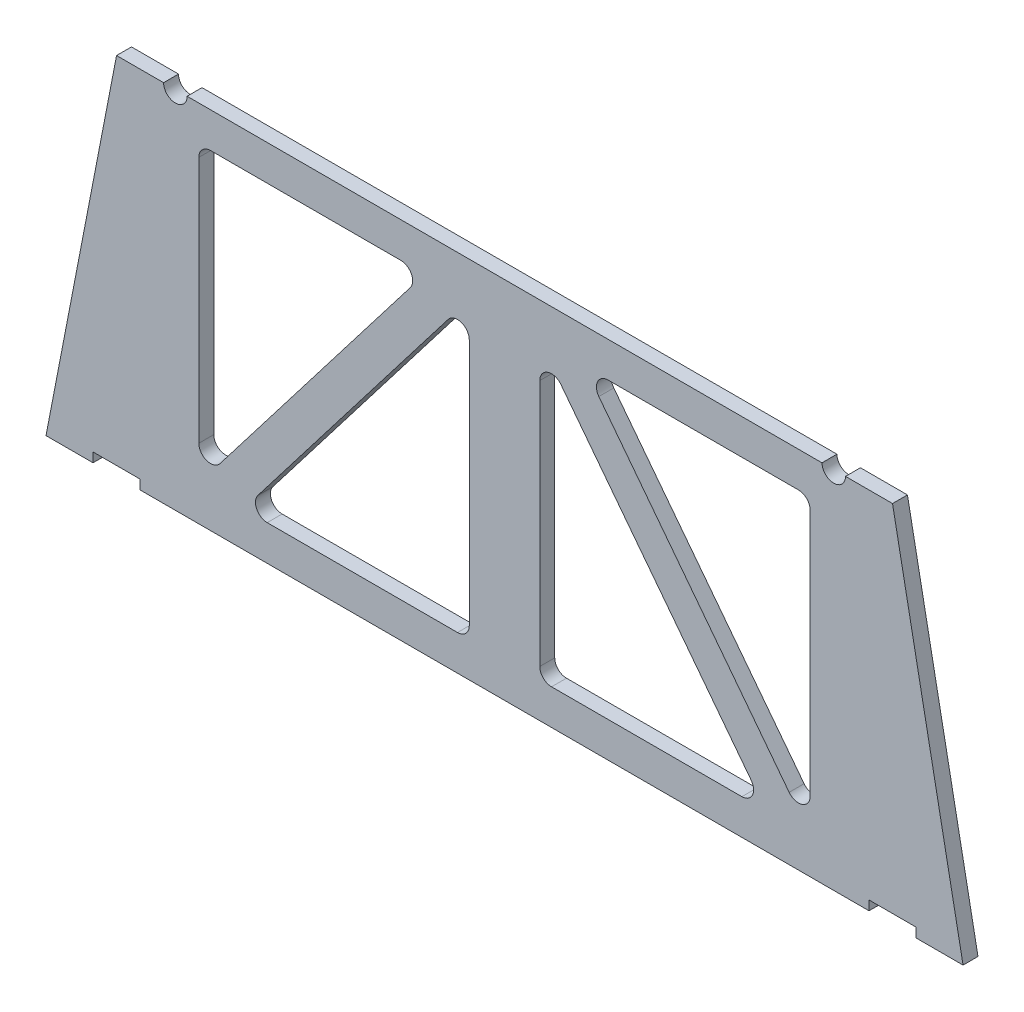
SolidWorks part; units mm, degrees
ref_plane "Front Plane" through (0, 0, 0) normal (0, 0, 1) x (1, 0, 0)
ref_plane "Top Plane" through (0, 0, 0) normal (0, 1, 0) x (1, 0, 0)
ref_plane "Right Plane" through (0, 0, 0) normal (1, 0, 0) x (0, 0, -1)
sketch "Sketch1" plane through (0, 0, 0) normal (0, 0, 1) x (1, 0, 0)
  line L0 (-155, -77.5) -> (155, -77.5)
  line L1 (195, -77.5) -> (165, 77.5)
  line L2 (165, 77.5) -> (145, 77.5)
  line L3 (-165, 77.5) -> (-195, -77.5)
  line L4 (-195, -77.5) -> (-175, -77.5)
  line L5 (-175, -77.5) -> (-175, -73.5)
  line L6 (-175, -73.5) -> (-155, -73.5)
  line L7 (-155, -73.5) -> (-155, -77.5)
  line L8 (-165, 77.5) -> (-145, 77.5)
  line L9 (155, -77.5) -> (155, -73.5)
  line L10 (155, -73.5) -> (175, -73.5)
  line L11 (175, -73.5) -> (175, -77.5)
  line L12 (175, -77.5) -> (195, -77.5)
  line L13 (-165, 77.5) -> (-145, 77.5)
  line L14 (0, -77.5) -> (0, 77.5) construction
  line L15 (-135, 77.5) -> (135, 77.5)
  line L16 (-130, 57.5) -> (-130, -47.7905)
  line L17 (-121.0358, -50.8376) -> (-40.1045, 54.4529)
  line L18 (-125, 62.5) -> (-44.0688, 62.5)
  line L19 (-104.8955, -54.4529) -> (-23.9642, 50.8376)
  line L20 (-15, 47.7905) -> (-15, -57.5)
  line L21 (-100.9312, -62.5) -> (-20, -62.5)
  line L22 (20, -62.5) -> (100.9312, -62.5)
  line L23 (15, 47.7905) -> (15, -57.5)
  line L24 (104.8955, -54.4529) -> (23.9642, 50.8376)
  line L25 (44.0688, 62.5) -> (125, 62.5)
  line L26 (121.0358, -50.8376) -> (40.1045, 54.4529)
  line L27 (130, 57.5) -> (130, -47.7905)
  arc A0 (-145, 77.5) -> (-135, 77.5) centre (-140, 77.5) ccw
  arc A1 (145, 77.5) -> (135, 77.5) centre (140, 77.5) cw
  arc A2 (-130, 57.5) -> (-125, 62.5) centre (-125, 57.5) cw
  arc A3 (-121.0358, -50.8376) -> (-130, -47.7905) centre (-125, -47.7905) cw
  arc A4 (-40.1045, 54.4529) -> (-44.0688, 62.5) centre (-44.0688, 57.5) ccw
  arc A5 (-15, 47.7905) -> (-23.9642, 50.8376) centre (-20, 47.7905) ccw
  arc A6 (-20, -62.5) -> (-15, -57.5) centre (-20, -57.5) ccw
  arc A7 (-100.9312, -62.5) -> (-104.8955, -54.4529) centre (-100.9312, -57.5) cw
  arc A8 (15, 47.7905) -> (23.9642, 50.8376) centre (20, 47.7905) cw
  arc A9 (15, -57.5) -> (20, -62.5) centre (20, -57.5) ccw
  arc A10 (100.9312, -62.5) -> (104.8955, -54.4529) centre (100.9312, -57.5) ccw
  arc A11 (44.0688, 62.5) -> (40.1045, 54.4529) centre (44.0688, 57.5) ccw
  arc A12 (130, 57.5) -> (125, 62.5) centre (125, 57.5) ccw
  arc A13 (121.0358, -50.8376) -> (130, -47.7905) centre (125, -47.7905) ccw
  point P15 (0, -77.5)
  point P29 (0, 0)
  point P37 (-130, 62.5)
  point P40 (-130, -62.5)
  point P43 (-33.9191, 62.5)
  point P46 (-15, 62.5)
  point P49 (-15, -62.5)
  point P52 (-111.0809, -62.5)
  point P55 (15, 62.5)
  point P58 (15, -62.5)
  point P61 (111.0809, -62.5)
  point P64 (33.9191, 62.5)
  point P67 (130, 62.5)
  point P70 (130, -62.5)
  dimension "D18" = 5
  dimension "D1" = 20
  dimension "D2" = 20
  dimension "D3" = 20
  dimension "D4" = 20
  dimension "D5" = 15
  dimension "D6" = 20
  dimension "D7" = 20
  dimension "D8" = 4
  dimension "D9" = 10
  dimension "D10" = 310
  dimension "D11" = 5
  dimension "D12" = 10
  dimension "D13" = 15
  dimension "D14" = 15
  dimension "D15" = 15
  dimension "D16" = 155
  dimension "D17" = 5
extrude "Extrude1" add sketch "Sketch1" along normal blind 6.35 contours L0 L14 L15 A0 L8 L3 L4 L5 L6 L7 L16 L18 L17 L21 L19 L20 | L14 L0 L9 L10 L11 L12 L1 L2 A1 L15 L25 L27 L26 L24 L22 L23
